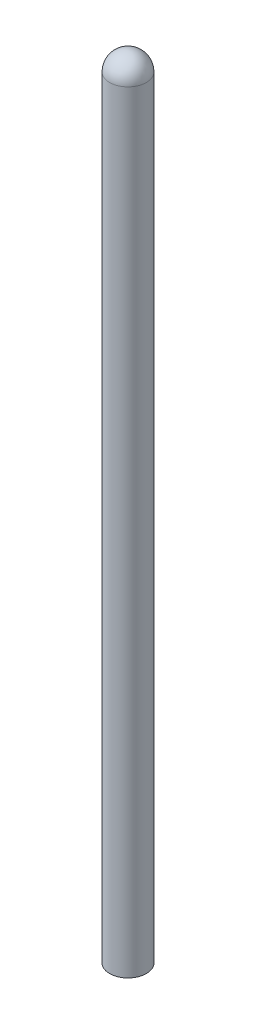
SolidWorks part; units mm, degrees
ref_plane "Front Plane" through (0, 0, 0) normal (0, 0, 1) x (1, 0, 0)
ref_plane "Top Plane" through (0, 0, 0) normal (0, 1, 0) x (1, 0, 0)
ref_plane "Right Plane" through (0, 0, 0) normal (1, 0, 0) x (0, 0, -1)
sketch "Sketch2" plane through (0, 0, 0) normal (0, 1, 0) x (1, 0, 0)
  circle A0 centre (0, 0) radius 2.5
  dimension "D1" = 5
extrude "Boss-Extrude1" add sketch "Sketch2" along normal blind 105
sketch "Sketch3" plane through (0, 0, 0) normal (1, 0, 0) x (0, 0, -1)
  line L0 (2.5, 105) -> (-2.5, 105) construction
  line L1 (-2.5, 105) -> (2.5, 105)
  arc A0 (2.5, 105) -> (-2.5, 105) centre (0, 105) ccw
revolve "Revolve1" add sketch "Sketch3" angle 360 about L1
